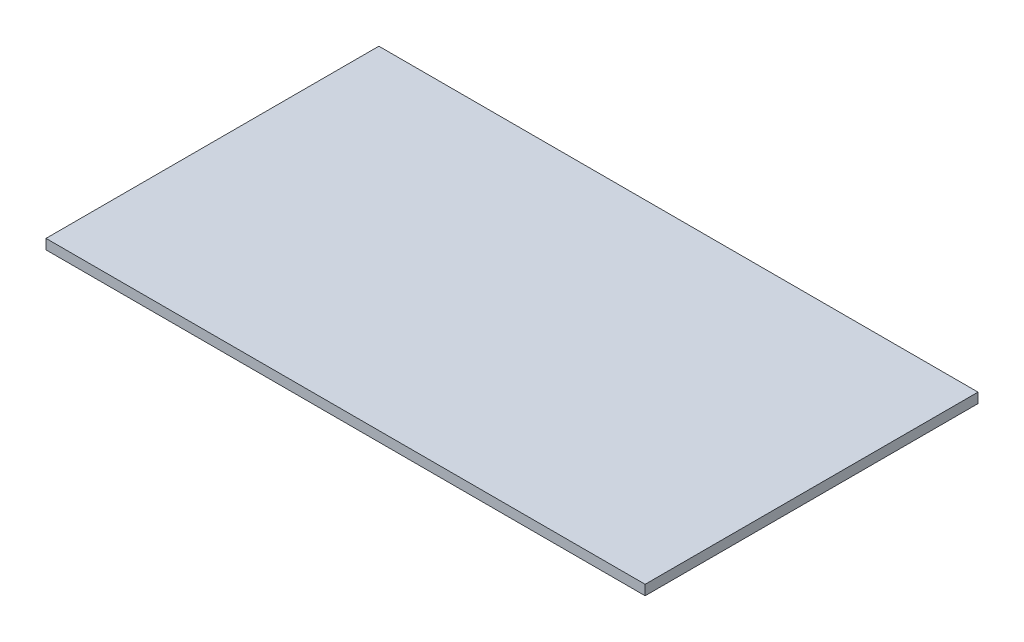
SolidWorks part; units mm, degrees
ref_plane "Front Plane" through (0, 0, 0) normal (0, 0, 1) x (1, 0, 0)
ref_plane "Top Plane" through (0, 0, 0) normal (0, 1, 0) x (1, 0, 0)
ref_plane "Right Plane" through (0, 0, 0) normal (1, 0, 0) x (0, 0, -1)
sketch "Sketch1" plane through (0, 0, 0) normal (0, 1, 0) x (1, 0, 0)
  line L1 (0, 0) -> (90, 0)
  line L2 (0, 0) -> (0, 50)
  line L3 (0, 50) -> (90, 50)
  line L4 (90, 0) -> (90, 50)
  dimension "D1" = 90
  dimension "D2" = 50
extrude "Boss-Extrude1" add sketch "Sketch1" along normal blind 1.5
